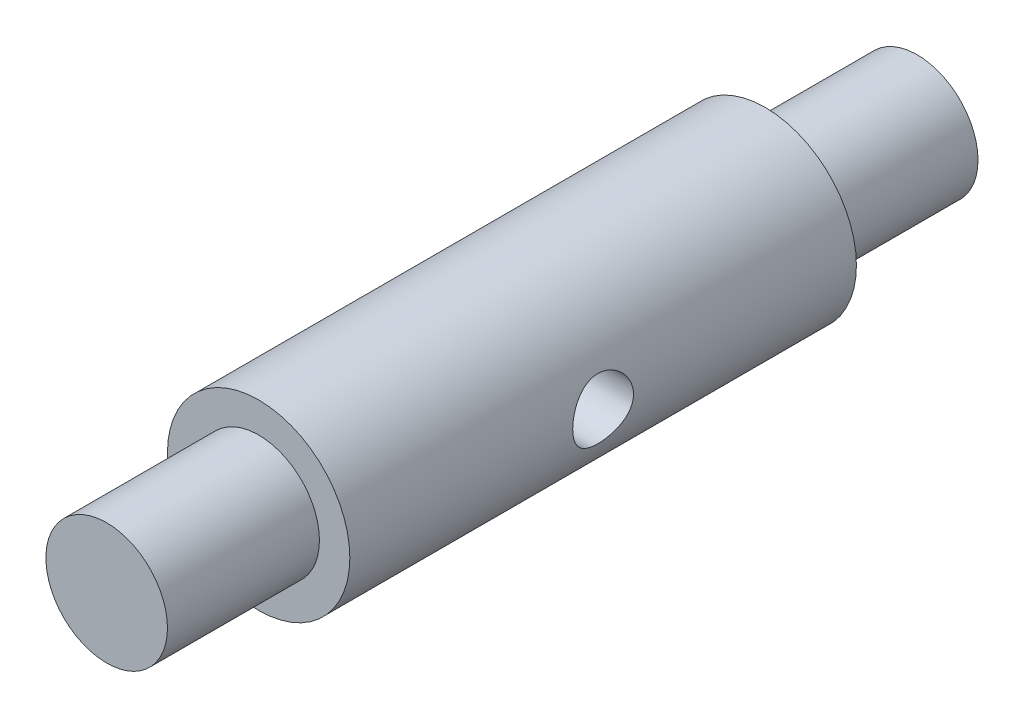
SolidWorks part; units mm, degrees
ref_plane "Front Plane" through (0, 0, 0) normal (0, 0, 1) x (1, 0, 0)
ref_plane "Top Plane" through (0, 0, 0) normal (0, 1, 0) x (1, 0, 0)
ref_plane "Right Plane" through (0, 0, 0) normal (1, 0, 0) x (0, 0, -1)
sketch "Sketch1" plane through (0, 0, 0) normal (0, 0, 1) x (1, 0, 0)
  circle A0 centre (0, 0) radius 9
  dimension "D1" = 18
extrude "Boss-Extrude1" add sketch "Sketch1" along normal mid plane 50
sketch "Sketch2" plane through (0, 0, 0) normal (0, 0, 1) x (1, 0, 0)
  circle A0 centre (0, 0) radius 6
  dimension "D1" = 12
extrude "Boss-Extrude2" add sketch "Sketch2" along normal mid plane 80
sketch "Sketch3" plane through (0, 0, 0) normal (1, 0, 0) x (0, 0, -1)
  line L0 (-25, -9) -> (0, -9) construction
  line L1 (-25, 9) -> (-25, -9) construction
  line L2 (0, -9) -> (0, 16.2386) construction
  circle A0 centre (0, 0) radius 3
  dimension "D1" = 6
extrude "Cut-Extrude2" cut sketch "Sketch3" against normal through all both and the other way through all contours A0
